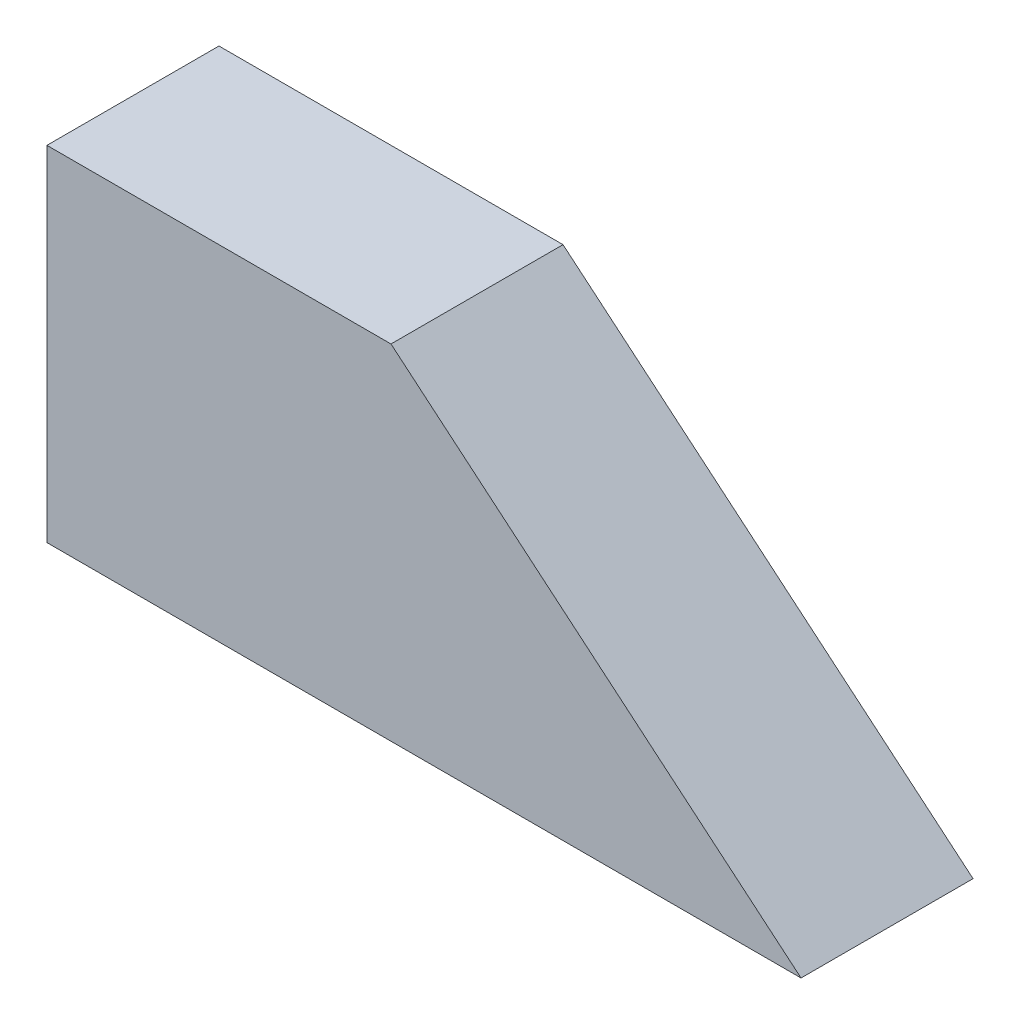
SolidWorks part; units mm, degrees
ref_plane "Front Plane" through (0, 0, 0) normal (0, 0, 1) x (1, 0, 0)
ref_plane "Top Plane" through (0, 0, 0) normal (0, 1, 0) x (1, 0, 0)
ref_plane "Right Plane" through (0, 0, 0) normal (1, 0, 0) x (0, 0, -1)
sketch "Sketch1" plane through (0, 0, 0) normal (0, 0, 1) x (1, 0, 0)
  line L0 (1000, 1000) -> (2191.7536, 0)
  line L1 (0, 0) -> (138.5594, 0)
  line L2 (0, 0) -> (0, 1000)
  line L3 (0, 1000) -> (1000, 1000)
  line L5 (2191.7536, 0) -> (138.5594, 0)
  dimension "D1" = 140
  dimension "D2" = 1000
  dimension "D3" = 1000
extrude "Boss-Extrude1" add sketch "Sketch1" along normal blind 500
